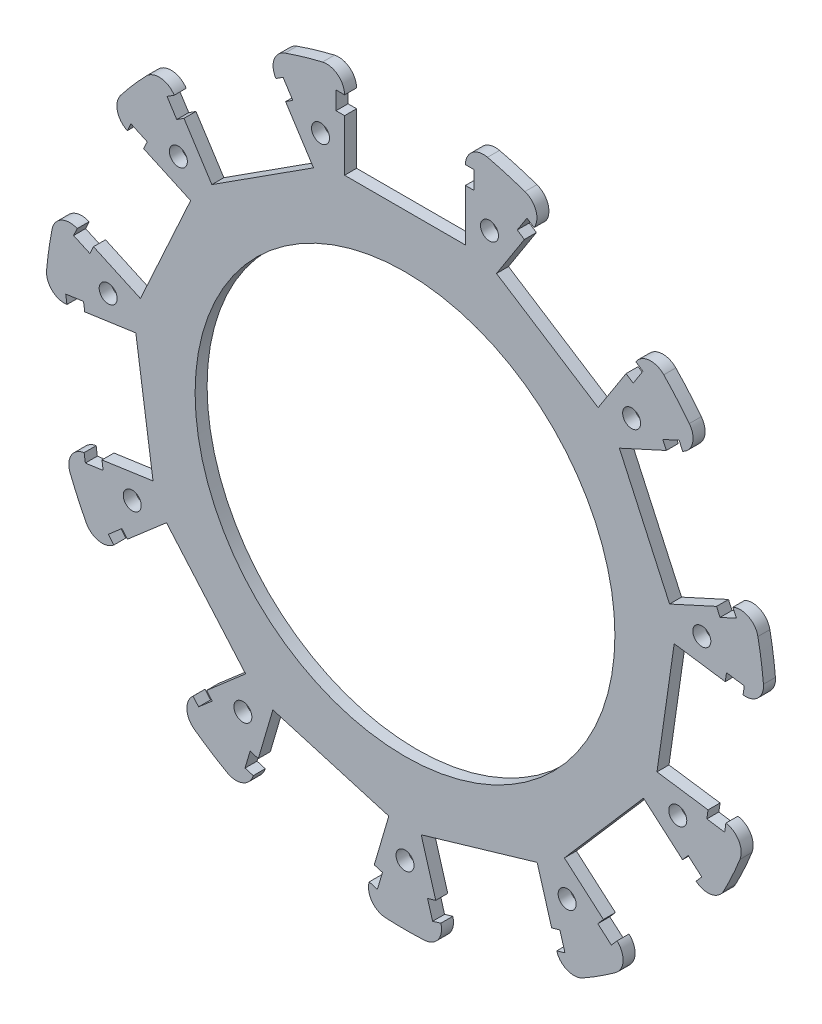
SolidWorks part; units mm, degrees
ref_plane "Front Plane" through (0, 0, 0) normal (0, 0, 1) x (1, 0, 0)
ref_plane "Top Plane" through (0, 0, 0) normal (0, 1, 0) x (1, 0, 0)
ref_plane "Right Plane" through (0, 0, 0) normal (1, 0, 0) x (0, 0, -1)
sketch "Sketch1" plane through (0, 0, 0) normal (0, 0, 1) x (1, 0, 0)
  line L44 (21.5207, 52.1193) -> (15.2567, 42.3722)
  line L47 (-10.0734, 55.4805) -> (-10.0734, 43.8941)
  line L48 (-10.0734, 43.8941) -> (10.0734, 43.8941)
  line L49 (10.0734, 55.4805) -> (10.0734, 43.8941)
  line L51 (38.4693, 41.2271) -> (32.2052, 31.48)
  line L52 (15.2567, 42.3722) -> (32.2052, 31.48)
  line L53 (46.2822, 32.2105) -> (35.7428, 27.3974)
  line L55 (54.6515, 13.8844) -> (44.1121, 9.0712)
  line L56 (35.7428, 27.3974) -> (44.1121, 9.0712)
  line L57 (56.3494, 2.0752) -> (44.8809, 3.7241)
  line L59 (53.4822, -17.8666) -> (42.0137, -16.2176)
  line L60 (44.8809, 3.7241) -> (42.0137, -16.2176)
  line L61 (48.526, -28.719) -> (39.7696, -21.1316)
  line L63 (35.3327, -43.945) -> (26.5763, -36.3575)
  line L64 (39.7696, -21.1316) -> (26.5763, -36.3575)
  line L65 (25.296, -50.3952) -> (22.0318, -39.2781)
  line L67 (5.9653, -56.0712) -> (2.701, -44.9541)
  line L68 (22.0318, -39.2781) -> (2.701, -44.9541)
  line L69 (-5.9653, -56.0712) -> (-2.701, -44.9541)
  line L71 (-25.296, -50.3952) -> (-22.0318, -39.2781)
  line L72 (-2.701, -44.9541) -> (-22.0318, -39.2781)
  line L73 (-35.3327, -43.945) -> (-26.5763, -36.3575)
  line L75 (-48.526, -28.719) -> (-39.7696, -21.1316)
  line L76 (-26.5763, -36.3575) -> (-39.7696, -21.1316)
  line L77 (-53.4822, -17.8666) -> (-42.0137, -16.2176)
  line L79 (-56.3494, 2.0752) -> (-44.8809, 3.7241)
  line L80 (-42.0137, -16.2176) -> (-44.8809, 3.7241)
  line L81 (-54.6515, 13.8844) -> (-44.1121, 9.0712)
  line L83 (-46.2822, 32.2105) -> (-35.7428, 27.3974)
  line L84 (-44.1121, 9.0712) -> (-35.7428, 27.3974)
  line L85 (-38.4693, 41.2271) -> (-32.2052, 31.48)
  line L87 (-21.5207, 52.1193) -> (-15.2567, 42.3722)
  line L88 (-32.2052, 31.48) -> (-15.2567, 42.3722)
  arc A33 (-43.1506, 41.6896) -> (-47.4063, 36.7783) centre (0, 0) ccw
  arc A34 (-13.7615, 58.4005) -> (-19.9968, 56.5697) centre (0, 0) ccw
  arc A35 (19.9968, 56.5697) -> (13.7615, 58.4005) centre (0, 0) ccw
  arc A36 (47.4063, 36.7783) -> (43.1506, 41.6896) centre (0, 0) ccw
  arc A37 (59.7646, 5.3101) -> (58.8397, 11.7426) centre (0, 0) ccw
  arc A38 (53.148, -27.844) -> (55.8476, -21.9327) centre (0, 0) ccw
  arc A39 (29.6574, -52.1578) -> (35.1243, -48.6444) centre (0, 0) ccw
  arc A40 (-3.2493, -59.912) -> (3.2493, -59.912) centre (0, 0) ccw
  arc A41 (-35.1243, -48.6444) -> (-29.6574, -52.1578) centre (0, 0) ccw
  arc A42 (-55.8476, -21.9327) -> (-53.148, -27.844) centre (0, 0) ccw
  arc A43 (-58.8397, 11.7426) -> (-59.7646, 5.3101) centre (0, 0) ccw
  arc A44 (-54.6515, 13.8844) -> (-58.8397, 11.7426) centre (-55.8977, 11.1555) ccw
  arc A45 (-56.3494, 2.0752) -> (-59.7646, 5.3101) centre (-56.7763, 5.0446) cw
  arc A46 (-48.526, -28.719) -> (-53.148, -27.844) centre (-50.4906, -26.4518) cw
  arc A47 (-53.4822, -17.8666) -> (-55.8476, -21.9327) centre (-53.0553, -20.836) ccw
  arc A48 (-25.296, -50.3952) -> (-29.6574, -52.1578) centre (-28.1745, -49.55) cw
  arc A49 (-35.3327, -43.945) -> (-35.1243, -48.6444) centre (-33.3681, -46.2122) ccw
  arc A50 (-5.9653, -56.0712) -> (-3.2493, -59.912) centre (-3.0868, -56.9164) ccw
  arc A51 (5.9653, -56.0712) -> (3.2493, -59.912) centre (3.0868, -56.9164) cw
  arc A52 (35.3327, -43.945) -> (35.1243, -48.6444) centre (33.3681, -46.2122) cw
  arc A53 (25.296, -50.3952) -> (29.6574, -52.1578) centre (28.1745, -49.55) ccw
  arc A54 (48.526, -28.719) -> (53.148, -27.844) centre (50.4906, -26.4518) ccw
  arc A55 (53.4822, -17.8666) -> (55.8476, -21.9327) centre (53.0553, -20.836) cw
  arc A56 (56.3494, 2.0752) -> (59.7646, 5.3101) centre (56.7763, 5.0446) ccw
  arc A57 (54.6515, 13.8844) -> (58.8397, 11.7426) centre (55.8977, 11.1555) cw
  arc A58 (46.2822, 32.2105) -> (47.4063, 36.7783) centre (45.036, 34.9394) ccw
  arc A59 (38.4693, 41.2271) -> (43.1506, 41.6896) centre (40.9931, 39.6052) cw
  arc A60 (21.5207, 52.1193) -> (19.9968, 56.5697) centre (18.997, 53.7412) ccw
  arc A61 (10.0734, 55.4805) -> (13.7615, 58.4005) centre (13.0734, 55.4805) cw
  arc A62 (-10.0734, 55.4805) -> (-13.7615, 58.4005) centre (-13.0734, 55.4805) ccw
  arc A63 (-21.5207, 52.1193) -> (-19.9968, 56.5697) centre (-18.997, 53.7412) cw
  arc A64 (-38.4693, 41.2271) -> (-43.1506, 41.6896) centre (-40.9931, 39.6052) ccw
  arc A65 (-46.2822, 32.2105) -> (-47.4063, 36.7783) centre (-45.036, 34.9394) cw
  point P3 (-57.9879, 15.408)
  point P51 (0, 0)
  point P55 (-57.1127, -18.3885)
  point P60 (-38.1047, -46.3469)
  point P63 (-6.9987, -59.5904)
  point P70 (26.3294, -53.9144)
  point P73 (51.298, -31.121)
  point P78 (59.9799, 1.5532)
  point P83 (49.6186, 33.7342)
  point P88 (23.5037, 55.2048)
  point P93 (-10.0734, 59.1483)
  dimension "D1" = 120
  dimension "D2" = 3
extrude "Boss-Extrude1" add sketch "Sketch1" along normal blind 2
sketch "Sketch2" plane through (0, 0, 2) normal (0, 0, 1) x (1, 0, 0)
  circle A0 centre (0, 0) radius 35
  dimension "D1" = 70
extrude "Cut-Extrude1" cut sketch "Sketch2" against normal through all
sketch "Sketch4" plane through (0, 0, 2) normal (0, 0, 1) x (1, 0, 0)
  line L0 (0, 17.7708) -> (0, 0) construction
  line L1 (0, 0) -> (-14.0866, 47.9746) construction
  circle A0 centre (-14.0866, 47.9746) radius 1.5
  circle A1 centre (14.0866, 47.9746) radius 1.5
  circle A2 centre (37.7875, 32.743) radius 1.5
  circle A3 centre (49.4911, 7.1157) radius 1.5
  circle A4 centre (45.4816, -20.7708) radius 1.5
  circle A5 centre (27.032, -42.0627) radius 1.5
  circle A6 centre (0, -50) radius 1.5
  circle A7 centre (-27.032, -42.0627) radius 1.5
  circle A8 centre (-45.4816, -20.7708) radius 1.5
  circle A9 centre (-49.4911, 7.1157) radius 1.5
  circle A10 centre (-37.7875, 32.743) radius 1.5
  point P28 (0, 0)
  dimension "D1" = 3
  dimension "D2" = 50
  dimension "D3" = 16.364
extrude "Cut-Extrude3" cut sketch "Sketch4" against normal blind 2
sketch "Sketch5" plane through (0, 0, 2) normal (0, 0, 1) x (1, 0, 0)
  line L0 (20.3311, 52.9069) -> (18.7092, 50.3832)
  line L1 (-11.5, 55.5) -> (11.5, 55.5)
  line L2 (-11.5, 55.5) -> (-11.5, 52.5)
  line L3 (-11.5, 52.5) -> (11.5, 52.5)
  line L4 (11.5, 55.5) -> (11.5, 52.5)
  line L5 (20.3311, 52.9069) -> (39.68, 40.4722)
  line L6 (39.68, 40.4722) -> (38.0581, 37.9484)
  line L7 (18.7092, 50.3832) -> (38.0581, 37.9484)
  line L8 (45.7073, 33.5163) -> (42.9784, 32.2701)
  line L9 (45.7073, 33.5163) -> (55.2618, 12.5948)
  line L10 (55.2618, 12.5948) -> (52.533, 11.3485)
  line L11 (42.9784, 32.2701) -> (52.533, 11.3485)
  line L12 (56.5717, 3.4845) -> (53.6022, 3.9114)
  line L13 (56.5717, 3.4845) -> (53.2985, -19.2814)
  line L14 (53.2985, -19.2814) -> (50.329, -18.8545)
  line L15 (53.6022, 3.9114) -> (50.329, -18.8545)
  line L16 (49.475, -27.6537) -> (47.2078, -25.6891)
  line L17 (49.475, -27.6537) -> (34.4132, -45.0359)
  line L18 (34.4132, -45.0359) -> (32.146, -43.0713)
  line L19 (47.2078, -25.6891) -> (32.146, -43.0713)
  line L20 (26.6703, -50.0119) -> (25.8251, -47.1335)
  line L21 (26.6703, -50.0119) -> (4.602, -56.4918)
  line L22 (4.602, -56.4918) -> (3.7568, -53.6133)
  line L23 (25.8251, -47.1335) -> (3.7568, -53.6133)
  line L24 (-4.602, -56.4918) -> (-3.7568, -53.6133)
  line L25 (-4.602, -56.4918) -> (-26.6703, -50.0119)
  line L26 (-26.6703, -50.0119) -> (-25.8251, -47.1335)
  line L27 (-3.7568, -53.6133) -> (-25.8251, -47.1335)
  line L28 (-34.4132, -45.0359) -> (-32.146, -43.0713)
  line L29 (-34.4132, -45.0359) -> (-49.475, -27.6537)
  line L30 (-49.475, -27.6537) -> (-47.2078, -25.6891)
  line L31 (-32.146, -43.0713) -> (-47.2078, -25.6891)
  line L32 (-53.2985, -19.2814) -> (-50.329, -18.8545)
  line L33 (-53.2985, -19.2814) -> (-56.5717, 3.4845)
  line L34 (-56.5717, 3.4845) -> (-53.6022, 3.9114)
  line L35 (-50.329, -18.8545) -> (-53.6022, 3.9114)
  line L36 (-55.2618, 12.5948) -> (-52.533, 11.3485)
  line L37 (-55.2618, 12.5948) -> (-45.7073, 33.5163)
  line L38 (-45.7073, 33.5163) -> (-42.9784, 32.2701)
  line L39 (-52.533, 11.3485) -> (-42.9784, 32.2701)
  line L40 (-39.68, 40.4722) -> (-38.0581, 37.9484)
  line L41 (-39.68, 40.4722) -> (-20.3311, 52.9069)
  line L42 (-20.3311, 52.9069) -> (-18.7092, 50.3832)
  line L43 (-38.0581, 37.9484) -> (-18.7092, 50.3832)
  point P4 (0, 55.5)
  point P49 (0, 0)
  dimension "D1" = 3
  dimension "D2" = 55.5
  dimension "D3" = 23
extrude "Cut-Extrude4" cut sketch "Sketch5" against normal through all contours L2 L1 L4 L3
